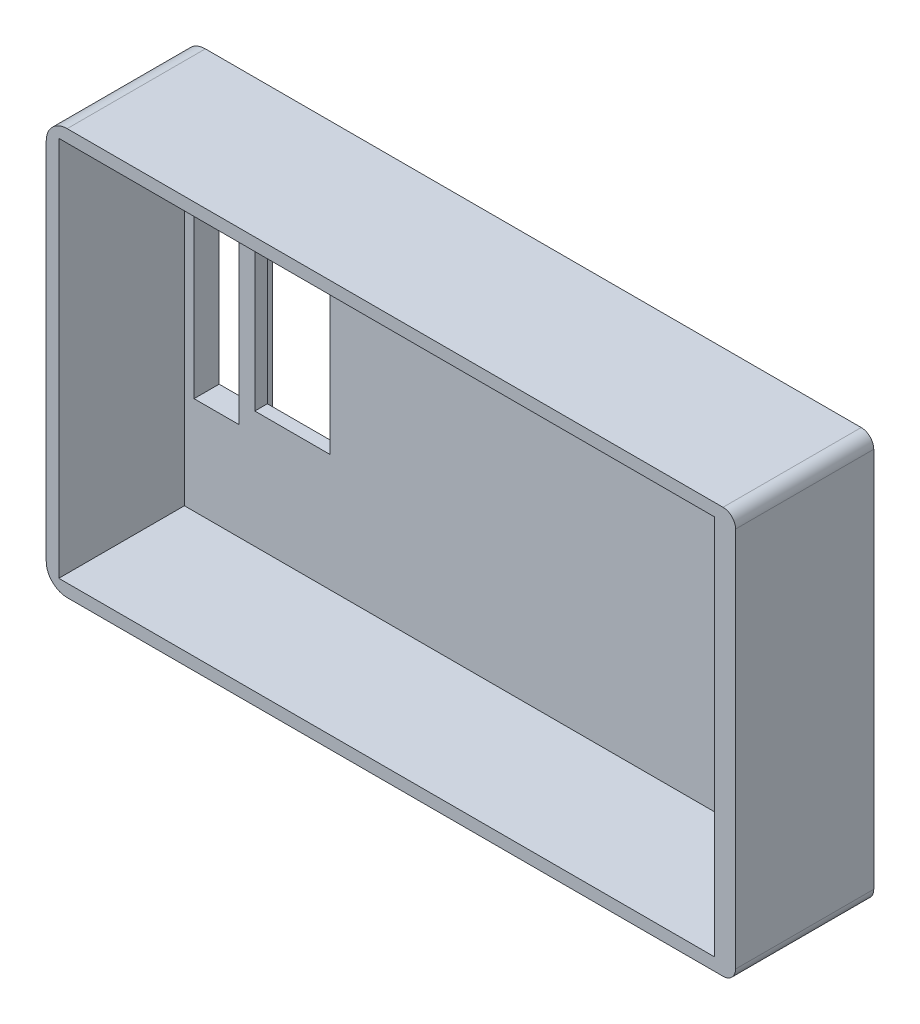
SolidWorks part; units mm, degrees
ref_plane "Alzado" through (0, 0, 0) normal (0, 0, 1) x (1, 0, 0)
ref_plane "Planta" through (0, 0, 0) normal (0, 1, 0) x (1, 0, 0)
ref_plane "Vista lateral" through (0, 0, 0) normal (1, 0, 0) x (0, 0, -1)
sketch "Croquis1" plane through (0, 0, 0) normal (0, 0, 1) x (1, 0, 0)
  line L0 (0, 97) -> (0, 0) construction
  line L1 (68.8143, 24) -> (53.5, 24)
  line L2 (68.8143, 24) -> (68.8143, 73)
  line L3 (68.8143, 73) -> (53.5, 73)
  line L4 (53.5, 24) -> (53.5, 73)
  line L5 (67.5143, 24.3) -> (54.8, 24.3)
  line L6 (68.5143, 25.3) -> (68.5143, 71.7)
  line L7 (67.5143, 72.7) -> (54.8, 72.7)
  line L8 (53.8, 25.3) -> (53.8, 71.7)
  line L9 (66.5143, 70.7) -> (55.8, 70.7)
  line L10 (66.5143, 70.7) -> (66.5143, 26.3)
  line L11 (66.5143, 26.3) -> (55.8, 26.3)
  line L12 (55.8, 70.7) -> (55.8, 26.3)
  line L13 (92.8154, 97) -> (-66.8143, 97) construction
  line L14 (-53.8, 25.3) -> (-53.8, 71.7)
  line L15 (-67.5143, 24.3) -> (-54.8, 24.3)
  line L16 (-53.5, 24) -> (-53.5, 73)
  line L17 (-68.8143, 24) -> (-53.5, 24)
  line L18 (-55.8, 70.7) -> (-55.8, 26.3)
  line L19 (-66.5143, 26.3) -> (-55.8, 26.3)
  line L20 (-66.5143, 70.7) -> (-66.5143, 26.3)
  line L21 (-66.5143, 70.7) -> (-55.8, 70.7)
  line L22 (-67.5143, 72.7) -> (-54.8, 72.7)
  line L23 (-68.5143, 25.3) -> (-68.5143, 71.7)
  line L24 (-68.8143, 73) -> (-53.5, 73)
  line L25 (-68.8143, 24) -> (-68.8143, 73)
  arc A0 (54.8, 72.7) -> (53.8, 71.7) centre (54.8, 71.7) ccw
  arc A1 (67.5143, 72.7) -> (68.5143, 71.7) centre (67.5143, 71.7) cw
  arc A2 (53.8, 25.3) -> (54.8, 24.3) centre (54.8, 25.3) ccw
  arc A3 (68.5143, 25.3) -> (67.5143, 24.3) centre (67.5143, 25.3) cw
  arc A4 (-53.8, 25.3) -> (-54.8, 24.3) centre (-54.8, 25.3) cw
  arc A5 (-68.5143, 25.3) -> (-67.5143, 24.3) centre (-67.5143, 25.3) ccw
  arc A6 (-67.5143, 72.7) -> (-68.5143, 71.7) centre (-67.5143, 71.7) ccw
  arc A7 (-54.8, 72.7) -> (-53.8, 71.7) centre (-54.8, 71.7) cw
  dimension "D9" = 1
  dimension "D1" = 0.3
  dimension "D2" = 0.3
  dimension "D3" = 0.3
  dimension "D4" = 0.3
  dimension "D5" = 2
  dimension "D6" = 2
  dimension "D7" = 2
  dimension "D8" = 2
extrude "Saliente-Extruir1" add sketch "Croquis1" against normal blind 3 contours A7 L22 A6 L23 A5 L15 A4 L14 L20 L21 L18 L19 | A3 L6 A1 L7 A0 L8 A2 L5 L12 L9 L10 L11
sketch "Croquis2" plane through (0, 0, 0) normal (0, 0, 1) x (1, 0, 0)
  line L0 (-52, 92) -> (-52, 5) construction
  line L1 (71.8143, 0) -> (-71.8143, 0)
  line L2 (71.8143, 0) -> (71.8143, 97)
  line L3 (71.8143, 97) -> (-71.8143, 97)
  line L4 (-71.8143, 0) -> (-71.8143, 97)
  line L5 (-52, 31) -> (-34.0355, 31)
  line L6 (-52, 31) -> (-52, 66)
  line L7 (-52, 66) -> (-34.0355, 66)
  line L8 (-34.0355, 31) -> (-34.0355, 66)
  line L9 (-71.8143, 48.5) -> (71.8143, 48.5) construction
  line L11 (66.5143, 26.3) -> (55.8, 26.3)
  line L12 (66.5143, 26.3) -> (66.5143, 70.7)
  line L13 (66.5143, 70.7) -> (55.8, 70.7)
  line L14 (55.8, 26.3) -> (55.8, 70.7)
  line L15 (-55.8, 26.3) -> (-66.5143, 26.3)
  line L16 (-55.8, 26.3) -> (-55.8, 70.7)
  line L17 (-55.8, 70.7) -> (-66.5143, 70.7)
  line L18 (-66.5143, 26.3) -> (-66.5143, 70.7)
  point P14 (-34.0355, 48.5)
  dimension "D1" = 35
extrude "Saliente-Extruir2" add sketch "Croquis2" along normal blind 3
sketch "Croquis3" plane through (0, 0, 3) normal (0, 0, 1) x (1, 0, 0)
  line L1 (71.8143, 0) -> (-71.8143, 0)
  line L2 (71.8143, 0) -> (71.8143, 97)
  line L3 (71.8143, 97) -> (-71.8143, 97)
  line L4 (-71.8143, 0) -> (-71.8143, 97)
  line L5 (68.8143, 3) -> (-68.8143, 3)
  line L6 (68.8143, 3) -> (68.8143, 94)
  line L7 (68.8143, 94) -> (-68.8143, 94)
  line L8 (-68.8143, 3) -> (-68.8143, 94)
  dimension "D1" = 3
  dimension "D2" = 3
  dimension "D3" = 3
  dimension "D4" = 3
extrude "Saliente-Extruir3" add sketch "Croquis3" along normal blind 30
fillet "Redondeo1" radius 5 4 edges at (71.8143, 0, 16.5) (-71.8143, 0, 16.5) (-71.8143, 97, 16.5) (71.8143, 97, 16.5)
sketch "Croquis4" plane through (71.8143, 0, 0) normal (1, 0, 0) x (0, 0, -1)
  line L1 (0, 0) -> (-35.0734, 0)
  line L2 (0, 0) -> (0, 97.2241)
  line L3 (0, 97.2241) -> (-35.0734, 97.2241)
  line L4 (-35.0734, 0) -> (-35.0734, 97.2241)
extrude "Cortar-Extruir1" cut sketch "Croquis4" against normal blind 5
sketch "Croquis6" plane through (0, 0, -3) normal (0, 0, -1) x (-1, 0, 0)
  line L0 (-66.5143, 70.7) -> (-55.8, 70.7) construction
  line L1 (-66.5143, 70.7) -> (-66.5143, 26.3) construction
  line L2 (-55.8, 70.7) -> (-55.8, 26.3) construction
  line L3 (-66.5143, 26.3) -> (-55.8, 26.3) construction
  line L4 (-67.5143, 24.3) -> (-54.8, 24.3)
  line L5 (-53.8, 25.3) -> (-53.8, 71.7)
  line L6 (-54.8, 72.7) -> (-67.5143, 72.7)
  line L7 (-68.5143, 71.7) -> (-68.5143, 25.3)
  line L8 (-67.5143, 24.3) -> (-54.8, 24.3)
  line L9 (-53.8, 25.3) -> (-53.8, 71.7)
  line L10 (-54.8, 72.7) -> (-67.5143, 72.7)
  line L11 (-68.5143, 71.7) -> (-68.5143, 25.3)
  line L12 (-66.5143, 70.7) -> (-55.8, 70.7)
  line L13 (-66.5143, 70.7) -> (-66.5143, 26.3)
  line L14 (-55.8, 70.7) -> (-55.8, 26.3)
  line L15 (-66.5143, 26.3) -> (-55.8, 26.3)
  arc A4 (-68.5143, 25.3) -> (-67.5143, 24.3) centre (-67.5143, 25.3) ccw
  arc A5 (-54.8, 24.3) -> (-53.8, 25.3) centre (-54.8, 25.3) ccw
  arc A6 (-53.8, 71.7) -> (-54.8, 72.7) centre (-54.8, 71.7) ccw
  arc A7 (-67.5143, 72.7) -> (-68.5143, 71.7) centre (-67.5143, 71.7) ccw
  arc A8 (-68.5143, 25.3) -> (-67.5143, 24.3) centre (-67.5143, 25.3) ccw
  arc A9 (-54.8, 24.3) -> (-53.8, 25.3) centre (-54.8, 25.3) ccw
  arc A10 (-53.8, 71.7) -> (-54.8, 72.7) centre (-54.8, 71.7) ccw
  arc A11 (-67.5143, 72.7) -> (-68.5143, 71.7) centre (-67.5143, 71.7) ccw
  dimension "D1" = 0
extrude "Cortar-Extruir2" cut sketch "Croquis6" against normal blind 3
sketch "Croquis7" plane through (55.8, 0, 0) normal (1, 0, 0) x (0, 0, -1)
  line L4 (-3, 26.3) -> (0, 26.3)
  line L5 (0, 26.3) -> (0, 70.7)
  line L6 (0, 70.7) -> (-3, 70.7)
  line L7 (-3, 70.7) -> (-3, 26.3)
  line L8 (-3, 26.3) -> (0, 26.3)
  line L9 (0, 26.3) -> (0, 70.7)
  line L10 (0, 70.7) -> (-3, 70.7)
  line L11 (-3, 70.7) -> (-3, 26.3)
  dimension "D1" = 0
extrude "Saliente-Extruir4" add sketch "Croquis7" along normal blind 11
sketch "Croquis8" plane through (66.8143, 0, 0) normal (1, 0, 0) x (0, 0, -1)
  line L8 (-33, 0) -> (0, 0)
  line L9 (0, 0) -> (0, 97)
  line L10 (0, 97) -> (-33, 97)
  line L11 (-33, 97) -> (-33, 94)
  line L12 (-33, 94) -> (-3, 94)
  line L13 (-3, 94) -> (-3, 3)
  line L14 (-3, 3) -> (-33, 3)
  line L15 (-33, 3) -> (-33, 0)
  line L16 (-33, 0) -> (0, 0)
  line L17 (0, 0) -> (0, 97)
  line L18 (0, 97) -> (-33, 97)
  line L19 (-33, 97) -> (-33, 94)
  line L20 (-33, 94) -> (-3, 94)
  line L21 (-3, 94) -> (-3, 3)
  line L22 (-3, 3) -> (-33, 3)
  line L23 (-33, 3) -> (-33, 0)
  dimension "D1" = 0
extrude "Saliente-Extruir5" add sketch "Croquis8" along normal blind 26
sketch "Croquis9" plane through (0, 0, 3) normal (0, 0, 1) x (1, 0, 0)
  line L0 (92.8143, 94) -> (-68.8143, 94) construction
  line L1 (92.8143, 3) -> (87.8143, 3)
  line L2 (92.8143, 3) -> (92.8143, 94)
  line L3 (92.8143, 94) -> (87.8143, 94)
  line L4 (87.8143, 3) -> (87.8143, 94)
  dimension "D1" = 5
extrude "Saliente-Extruir6" add sketch "Croquis9" along normal blind 30
fillet "Redondeo2" radius 3 2 edges at (92.8143, 0, 16.5) (92.8143, 97, 16.5)
